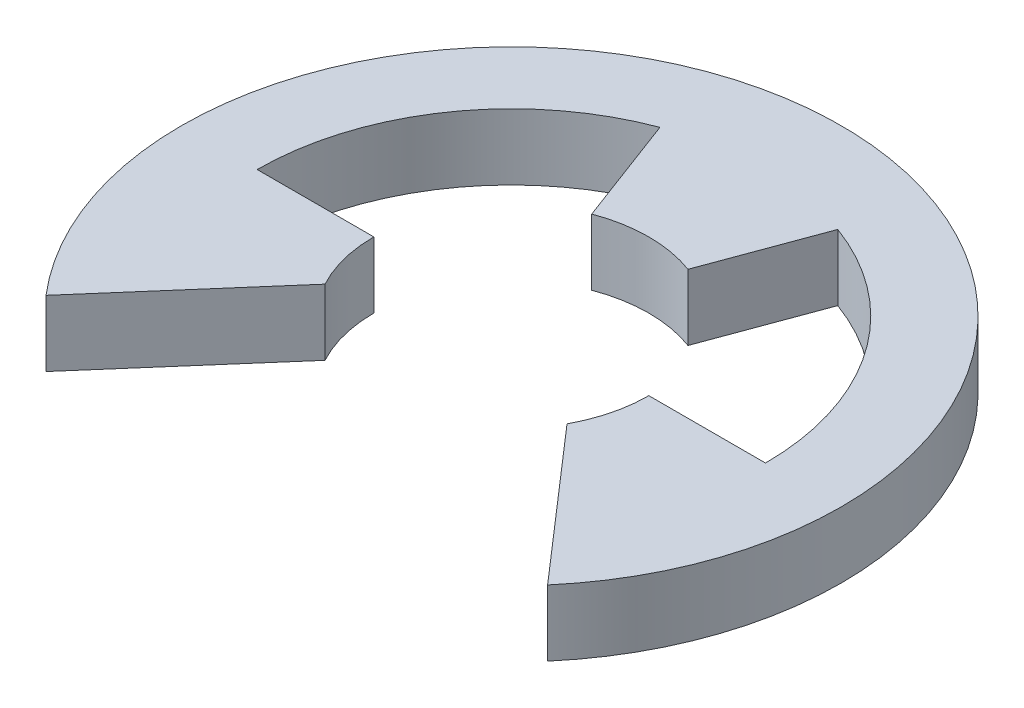
SolidWorks part; units mm, degrees
ref_plane "前视基准面" through (0, 0, 0) normal (0, 0, 1) x (1, 0, 0)
ref_plane "上视基准面" through (0, 0, 0) normal (0, 1, 0) x (1, 0, 0)
ref_plane "右视基准面" through (0, 0, 0) normal (1, 0, 0) x (0, 0, -1)
other "Configuration Table"
sketch "草图1" plane through (0, 0, 0) normal (0, 1, 0) x (1, 0, 0)
  line L1 (-1.1, -0.5937) -> (-2.2798, -1.95)
  line L2 (1.1, -0.5937) -> (2.2798, -1.95)
  line L3 (-0.4393, 1.1703) -> (-0.812, 2.1629)
  line L4 (0.4328, 1.1727) -> (0.7999, 2.1674)
  line L5 (-1.25, 0) -> (-2.3103, 0)
  line L6 (1.25, 0) -> (2.3103, 0)
  circle A0 centre (0, 0) radius 1.25 construction
  arc A1 (2.2798, -1.95) -> (-2.2798, -1.95) centre (0, 0) ccw
  arc A2 (-0.812, 2.1629) -> (-2.3103, 0) centre (0, 0) ccw
  arc A3 (2.3103, 0) -> (0.7999, 2.1674) centre (0, 0) ccw
  arc A4 (0.4328, 1.1727) -> (-0.4393, 1.1703) centre (0, 0) ccw
  arc A5 (-1.25, 0) -> (-1.1, -0.5937) centre (0, 0) ccw
  arc A6 (1.25, 0) -> (1.1, -0.5937) centre (0, 0) cw
  dimension "D1" = 2.5
  dimension "D2" = 6
  dimension "D3" = 2.2
extrude "凸台-拉伸1" add sketch "草图1" along normal blind 0.6
